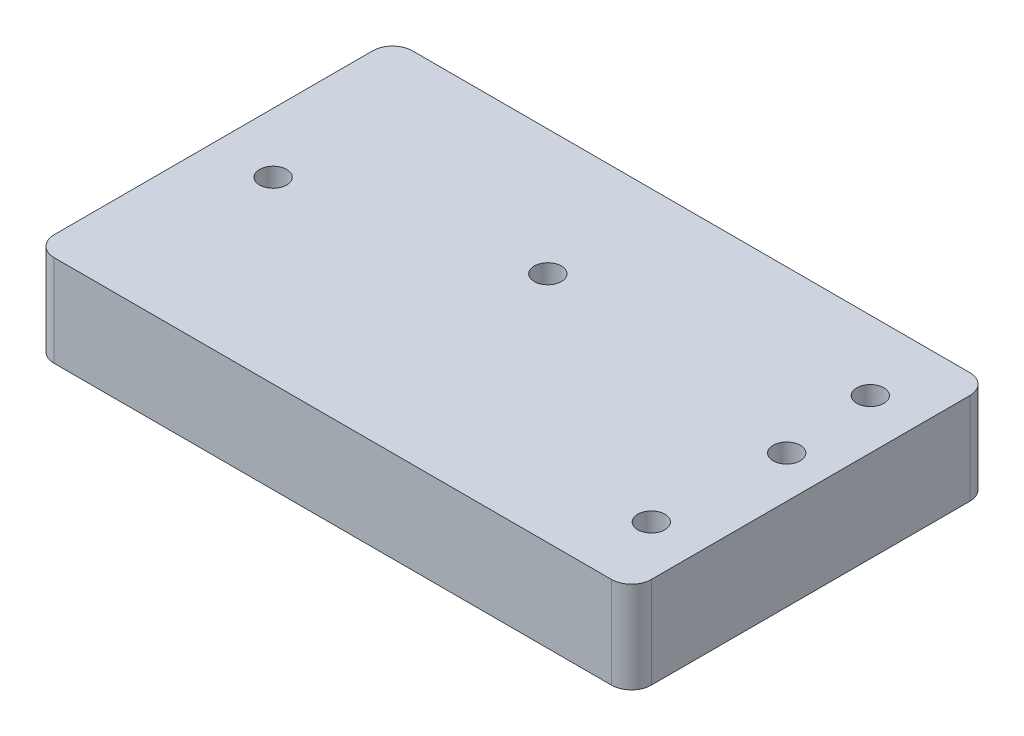
SolidWorks part; units mm, degrees
material "Free-Cutting Brass, UNS C36000"
ref_plane "Front Plane" through (0, 0, 0) normal (0, 0, 1) x (1, 0, 0)
ref_plane "Top Plane" through (0, 0, 0) normal (0, 1, 0) x (1, 0, 0)
ref_plane "Right Plane" through (0, 0, 0) normal (1, 0, 0) x (0, 0, -1)
sketch "Sketch2" plane through (0, 0, 0) normal (0, 1, 0) x (1, 0, 0)
  line L1 (0, 0) -> (76.2, 0)
  line L2 (0, 0) -> (0, -45.72)
  line L3 (0, -45.72) -> (76.2, -45.72)
  line L4 (76.2, 0) -> (76.2, -45.72)
  dimension "D1" = 76.2
  dimension "D2" = 45.72
extrude "Boss-Extrude3" add sketch "Sketch2" along normal blind 11.684
sketch "Sketch6" plane through (0, 11.684, 0) normal (0, 1, 0) x (1, 0, 0)
  circle A0 centre (7.62, -22.86) radius 1.7272
extrude "Cut-Extrude2" cut sketch "Sketch6" against normal through all
sketch "Sketch7" plane through (0, 11.684, 0) normal (0, 1, 0) x (1, 0, 0)
  circle A0 centre (69.85, -8.89) radius 1.7272
extrude "Cut-Extrude3" cut sketch "Sketch7" against normal through all
sketch "Sketch8" plane through (0, 11.684, 0) normal (0, 1, 0) x (1, 0, 0)
  circle A0 centre (69.85, -36.83) radius 1.7272
extrude "Cut-Extrude4" cut sketch "Sketch8" against normal through all
sketch "Sketch9" plane through (0, 0, 0) normal (-1, 0, 0) x (0, 0, 1)
  circle A0 centre (27.94, 9.017) radius 1.397
extrude "Cut-Extrude5" cut sketch "Sketch9" against normal blind 15.24
hole_wizard "#4-40 Tapped Hole1" positions "Sketch" profile "Sketch11" tap size "#4-40" standard "ANSI Inch"
sketch "Sketch" plane through (0, 0, 0) normal (0, -1, 0) x (-1, 0, 0)
  point P1 (-3.175, -3.5052)
  point P4 (-3.175, -3.5052)
  point P18 (-3.175, -37.1602)
  point P24 (-14.605, -3.5052)
  point P26 (-14.605, -37.1602)
sketch "Sketch11" plane through (3.175, 0, 3.5052) normal (1, 0, 0) x (0, 0, -1)
  line L0 (0, 0) -> (0, 8.2992)
  line L1 (0, 8.2992) -> (1.1303, 7.62)
  line L2 (1.1303, 7.62) -> (1.1303, 0)
  line L5 (1.1303, 0) -> (0, 0)
  line L10 (0, 8.2992) -> (-1.1303, 7.62) construction
  line L11 (0, -6.35) -> (0, 107.95) construction
  dimension "Tap Drill Dia." = 2.2606
  dimension "Tap Drill Depth" = 7.62
  dimension "Drill Angle" = 118
hole_wizard "#8-32 Tapped Hole1" positions "3DSketch1" profile "Sketch13" tap size "#8-32" standard "ANSI Inch"
sketch3d "3DSketch1"
  point P0 (70.866, 0, 20.574)
sketch "Sketch13" plane through (70.866, 0, 20.574) normal (1, 0, 0) x (0, 0, -1)
  line L0 (0, 0) -> (0, 13.4838)
  line L1 (0, 13.4838) -> (1.7272, 12.446)
  line L2 (1.7272, 12.446) -> (1.7272, 0)
  line L5 (1.7272, 0) -> (0, 0)
  line L10 (0, 13.4838) -> (-1.7272, 12.446) construction
  line L11 (0, -6.35) -> (0, 107.95) construction
  dimension "Tap Drill Dia." = 3.4544
  dimension "Tap Drill Depth" = 12.446
  dimension "Drill Angle" = 118
hole_wizard "#8-32 Tapped Hole2" positions "3DSketch2" profile "Sketch14" tap size "#8-32" standard "ANSI Inch"
sketch3d "3DSketch2"
  point P0 (35.814, 0, 16.002)
sketch "Sketch14" plane through (35.814, 0, 16.002) normal (1, 0, 0) x (0, 0, -1)
  line L0 (0, 0) -> (0, 13.4838)
  line L1 (0, 13.4838) -> (1.7272, 12.446)
  line L2 (1.7272, 12.446) -> (1.7272, 0)
  line L5 (1.7272, 0) -> (0, 0)
  line L10 (0, 13.4838) -> (-1.7272, 12.446) construction
  line L11 (0, -6.35) -> (0, 107.95) construction
  dimension "Tap Drill Dia." = 3.4544
  dimension "Tap Drill Depth" = 12.446
  dimension "Drill Angle" = 118
fillet "Fillet1" radius 2.54 4 edges at (0, 5.842, 0) (76.2, 5.842, 0) (0, 5.842, 45.72) (76.2, 5.842, 45.72)
